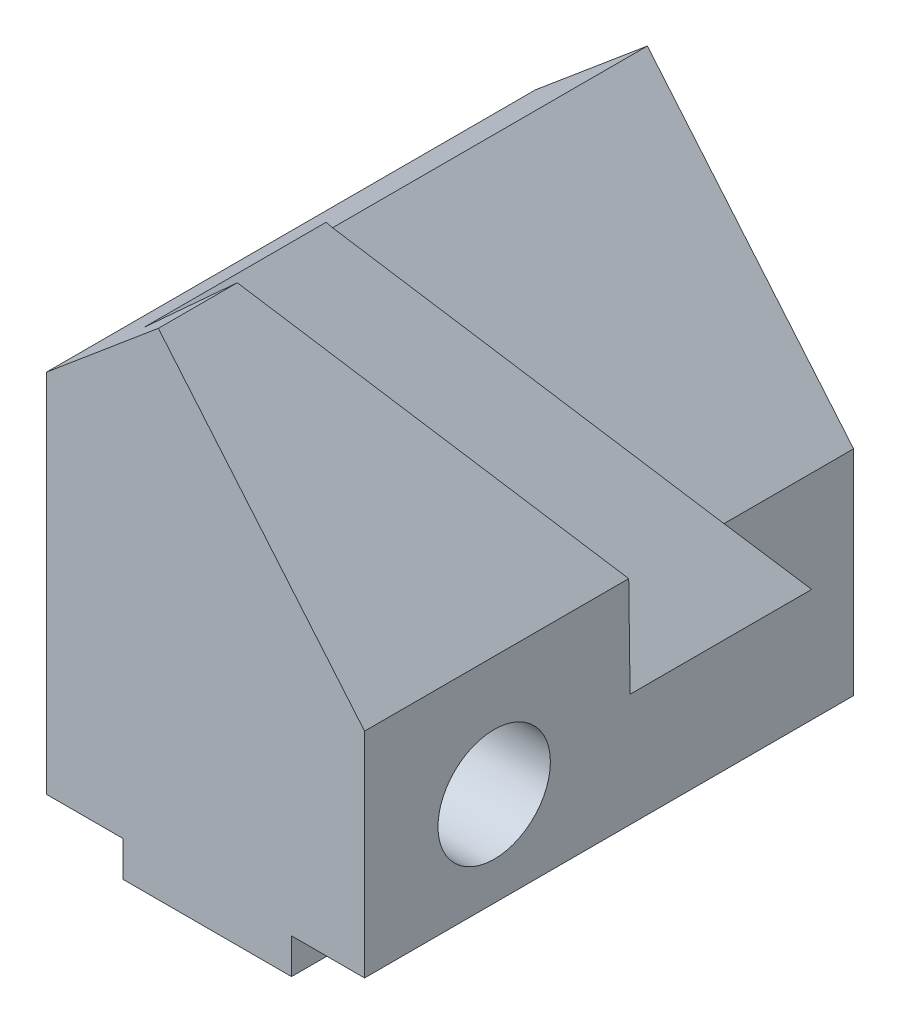
SolidWorks part; units mm, degrees
ref_plane "Front Plane" through (0, 0, 0) normal (0, 0, 1) x (1, 0, 0)
ref_plane "Top Plane" through (0, 0, 0) normal (0, 1, 0) x (1, 0, 0)
ref_plane "Right Plane" through (0, 0, 0) normal (1, 0, 0) x (0, 0, -1)
sketch "Sketch4" plane through (0, 0, 0) normal (0, 0, 1) x (1, 0, 0)
  line L0 (14.6, 0) -> (-14, 0)
  line L1 (-14, 0) -> (-14, 6)
  line L2 (-14, 6) -> (-27, 6)
  line L3 (-27, 6) -> (-27, 84)
  line L4 (14.6, 0) -> (14.6, 6)
  line L5 (14.6, 6) -> (27, 6)
  line L6 (27, 6) -> (27, 84)
  line L7 (27, 84) -> (-27, 84)
  line L8 (55, 0) -> (-55, 0) construction
  line L9 (0, -76.2787) -> (0, 76.2787) construction
  point P10 (0, 84)
  dimension "D1" = 28.6
  dimension "D2" = 6
  dimension "D3" = 13
  dimension "D4" = 78
  dimension "D5" = 54
extrude "Front Plane Extruded Boss" add sketch "Sketch4" along normal blind 83
sketch "Sketch5" plane through (0, 0, 83) normal (0, 0, 1) x (1, 0, 0)
  line L0 (-27, 84) -> (-8, 84)
  line L1 (27, 84) -> (-27, 84) construction
  line L2 (-8, 84) -> (-27, 68.0571)
  line L3 (-27, 84) -> (-27, 6) construction
  line L4 (-27, 68.0571) -> (-27, 84)
  dimension "D1" = 40
  dimension "D2" = 19
extrude "Smaller Triangular Extruded Cut" cut sketch "Sketch5" against normal through all
sketch "Sketch6" plane through (0, 0, 83) normal (0, 0, 1) x (1, 0, 0)
  line L0 (27, 84) -> (-8, 84)
  line L1 (-8, 84) -> (27, 42.2886)
  line L2 (27, 6) -> (27, 84) construction
  line L3 (27, 42.2886) -> (27, 84)
  dimension "D1" = 50
extrude "Bigger Triangular Extruded Cut" cut sketch "Sketch6" against normal through all
hole_wizard "19.075D Hole" positions "Sketch7" profile "Sketch8" hole size "1/16" standard "ANSI Inch" end condition through all
sketch "Sketch7" plane through (27, 0, 0) normal (1, 0, 0) x (0, 0, -1)
  line L0 (-83, 6) -> (-83, 42.2886) construction
  line L6 (-83, 6) -> (0, 6) construction
  point P0 (-61, 22)
  dimension "D1" = 22
  dimension "D2" = 16
sketch "Sketch8" plane through (27, 22, 61) normal (0, 1, 0) x (0, 0, -1)
  line L0 (0, 0) -> (0, 54)
  line L1 (0, 54) -> (9.5375, 54)
  line L2 (9.5375, 54) -> (9.5375, 0)
  line L5 (9.5375, 0) -> (0, 0)
  line L11 (0, -6.35) -> (0, 107.95) construction
  dimension "Thru Hole Dia." = 19.075
  dimension "Thru Hole Depth" = 54
sketch "Surface B Dovetail Cut Position" plane through (36.6673, 30.7675, 0) normal (0.766, 0.6428, 0) x (0, 0, -1)
  line L0 (-22, 15.0397) -> (-53.4369, 69.49)
  line L1 (0, 15.0397) -> (-83, 15.0397) construction
  line L2 (0, 69.49) -> (-83, 69.49) construction
  line L3 (0, 79.7607) -> (0, -79.7607) construction
  dimension "D1" = 22
  dimension "D2" = 30
ref_plane "Plane A" through (-8, 84, 53.4369) normal (-0.5567, 0.6634, 0.5) x (0.8307, 0.4446, 0.335)
sketch "Sketch13" plane through (-8, 84, 53.4369) normal (-0.5567, 0.6634, 0.5) x (0.8307, 0.4446, 0.335)
  line L0 (0, 0) -> (-12.6004, 1.6006)
  line L1 (-17.9039, 42.6741) -> (9.905, -23.6087) construction
  line L2 (-12.6004, 1.6006) -> (-2.2701, -23.0218)
  line L3 (-2.2701, -23.0218) -> (5.4163, -12.9098)
  line L4 (5.4163, -12.9098) -> (0, 0)
  dimension "D1" = 14
  dimension "D2" = 11
  dimension "D3" = 60
extrude "Dovetail Extruded Cut" cut sketch "Sketch13" against normal through all and the other way through all
